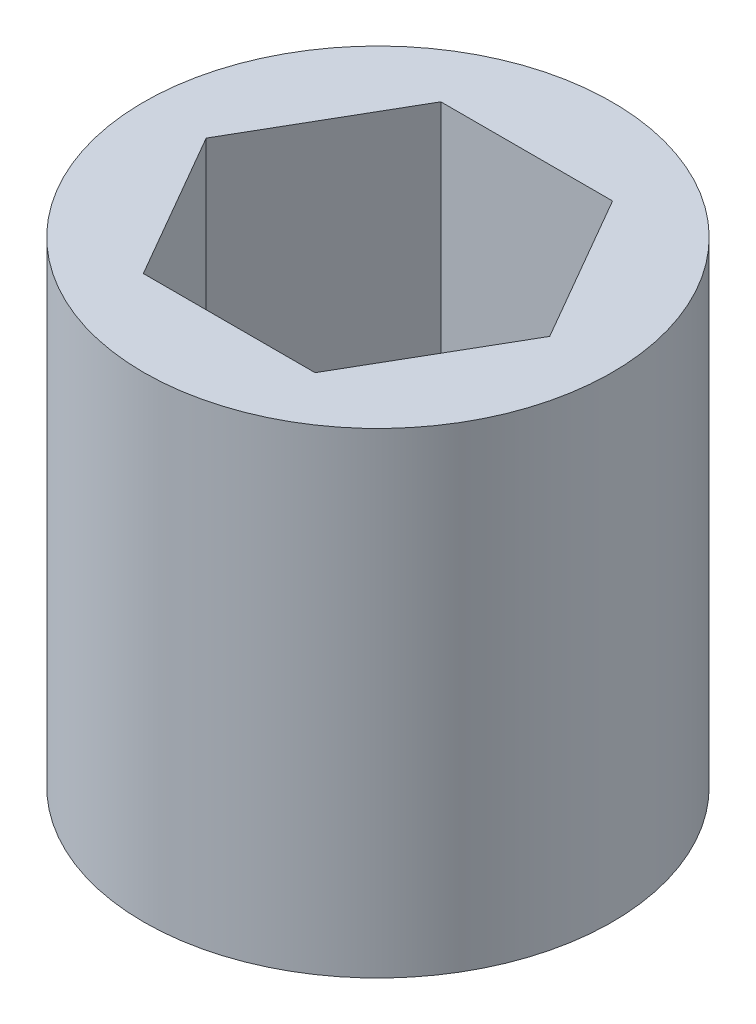
SolidWorks part; units mm, degrees
ref_plane "Front Plane" through (0, 0, 0) normal (0, 0, 1) x (1, 0, 0)
ref_plane "Top Plane" through (0, 0, 0) normal (0, 1, 0) x (1, 0, 0)
ref_plane "Right Plane" through (0, 0, 0) normal (1, 0, 0) x (0, 0, -1)
sketch "Sketch1" plane through (0, 0, 0) normal (0, 1, 0) x (1, 0, 0)
  line L1 (-7.3323, 0) -> (-3.6662, -6.35)
  line L2 (-3.6662, -6.35) -> (3.6662, -6.35)
  line L3 (3.6662, -6.35) -> (7.3323, 0)
  line L4 (7.3323, 0) -> (3.6662, 6.35)
  line L5 (3.6662, 6.35) -> (-3.6662, 6.35)
  line L6 (-3.6662, 6.35) -> (-7.3323, 0)
  circle A0 centre (0, 0) radius 10
  circle A1 centre (0, 0) radius 6.35 construction
  dimension "D2" = 20
  dimension "D1" = 12.7
extrude "Boss-Extrude1" add sketch "Sketch1" along normal blind 20.32
